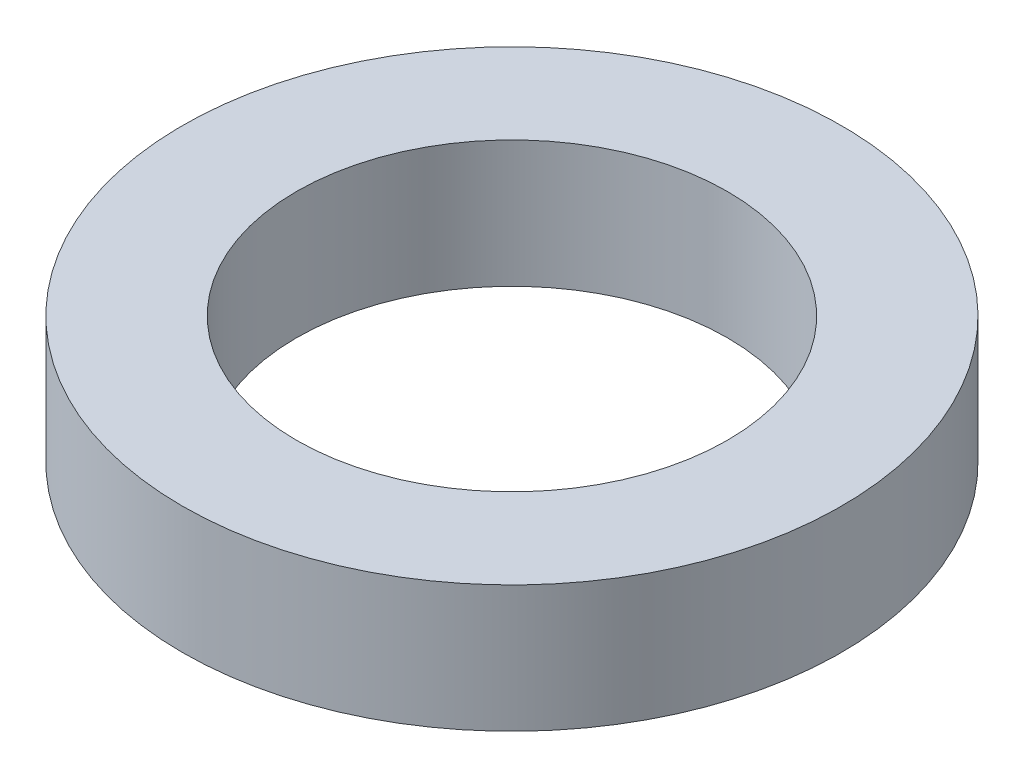
SolidWorks part; units mm, degrees
ref_plane "前视基准面" through (0, 0, 0) normal (0, 0, 1) x (1, 0, 0)
ref_plane "上视基准面" through (0, 0, 0) normal (0, 1, 0) x (1, 0, 0)
ref_plane "右视基准面" through (0, 0, 0) normal (1, 0, 0) x (0, 0, -1)
other "Configuration Table"
sketch "草图1" plane through (0, 0, 0) normal (0, 1, 0) x (1, 0, 0)
  circle A0 centre (0, 0) radius 8.5
  circle A1 centre (0, 0) radius 13
  dimension "D1" = 17
  dimension "D2" = 26
extrude "凸台-拉伸1" add sketch "草图1" along normal blind 5
